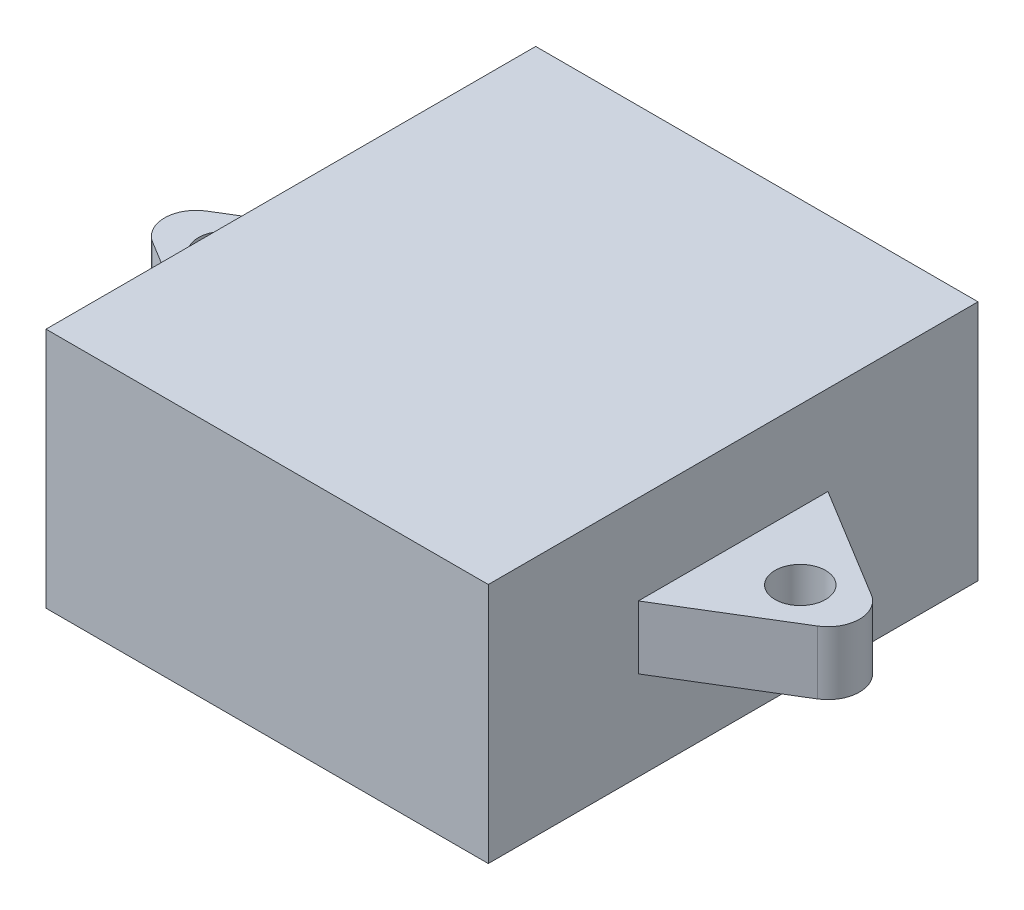
SolidWorks part; units mm, degrees
ref_plane "前视基准面" through (0, 0, 0) normal (0, 0, 1) x (1, 0, 0)
ref_plane "上视基准面" through (0, 0, 0) normal (0, 1, 0) x (1, 0, 0)
ref_plane "右视基准面" through (0, 0, 0) normal (1, 0, 0) x (0, 0, -1)
other "Configuration Table"
sketch "草图1" plane through (0, 0, 0) normal (0, 1, 0) x (1, 0, 0)
  line L1 (-14, -18.7017) -> (14, -18.7017)
  line L2 (-14, -18.7017) -> (-14, 12.2983)
  line L3 (-14, 12.2983) -> (14, 12.2983)
  line L4 (14, -18.7017) -> (14, 12.2983)
  line L5 (-14, -18.7017) -> (14, 12.2983) construction
  line L6 (-14, 12.2983) -> (14, -18.7017) construction
  point P0 (0, -3.2017)
  dimension "D1" = 28
  dimension "D2" = 31
extrude "凸台-拉伸1" add sketch "草图1" along normal blind 15.3
ref_plane "基准面1" through (0, 7.65, 0) normal (0, 1, 0) x (1, 0, 0)
sketch "草图2" plane through (0, 7.65, 0) normal (0, 1, 0) x (1, 0, 0)
  line L0 (-14, -3.2017) -> (22, -3.2017) construction
  line L1 (-14, 12.2983) -> (-14, -18.7017) construction
  line L2 (0, 12.2983) -> (0, -18.7017) construction
  line L3 (14, 12.2983) -> (-14, 12.2983) construction
  line L4 (-14, -18.7017) -> (14, -18.7017) construction
  line L5 (18.25, 3.6161) -> (18.25, -12.6093) construction
  line L6 (14, 2.7983) -> (21.041, -1.494)
  line L7 (14, -18.7017) -> (14, 12.2983) construction
  line L8 (21.041, -4.9094) -> (14, -9.2017)
  line L9 (20, 0.144) -> (20, -5.651) construction
  line L10 (14, 2.7983) -> (14, -9.2017)
  circle A0 centre (18.25, -3.2017) radius 1.6
  arc A1 (21.041, -1.494) -> (21.041, -4.9094) centre (20, -3.2017) cw
  dimension "D3" = 3.2
  dimension "D4" = 2
  dimension "D1" = 22
  dimension "D2" = 18.25
  dimension "D5" = 2
  dimension "D6" = 6
  dimension "D7" = 6
extrude "凸台-拉伸2" add sketch "草图2" along normal blind 2 and the other way blind 2
mirror "镜向1" about plane through (0, 0, 0) normal (1, 0, 0) of "凸台-拉伸2"
